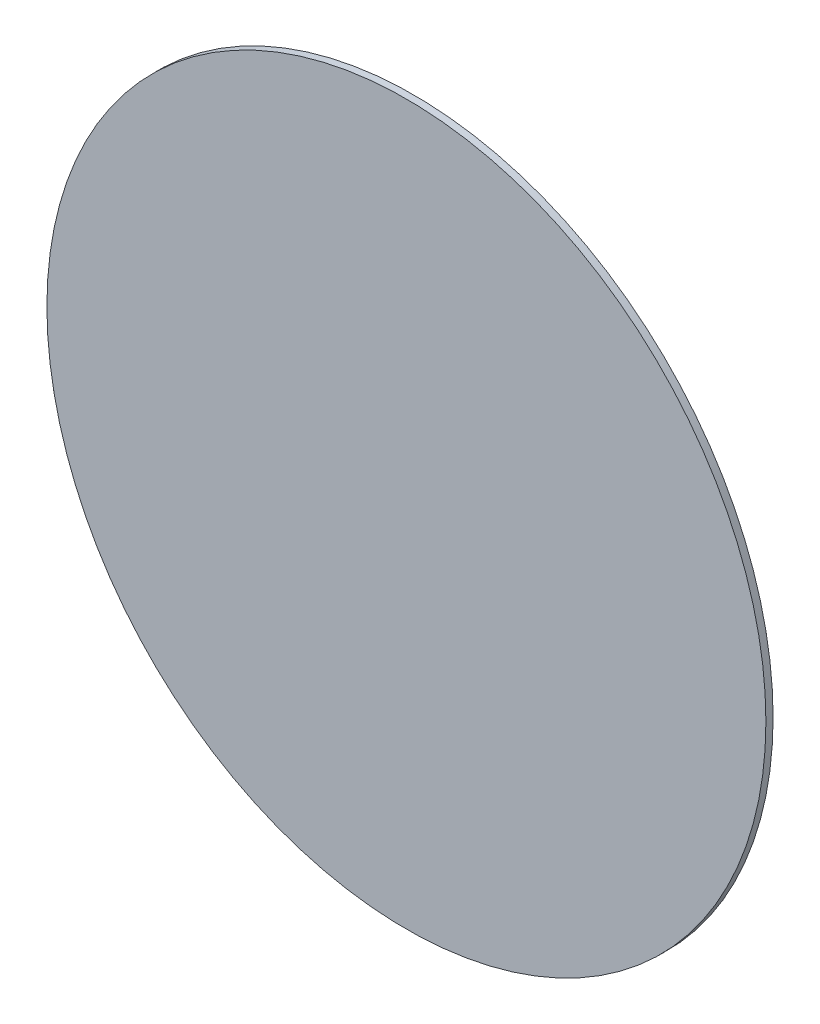
SolidWorks part; units mm, degrees
material "瓦楞纸"
ref_plane "前视基准面" through (0, 0, 0) normal (0, 0, 1) x (1, 0, 0)
ref_plane "上视基准面" through (0, 0, 0) normal (0, 1, 0) x (1, 0, 0)
ref_plane "右视基准面" through (0, 0, 0) normal (1, 0, 0) x (0, 0, -1)
sketch "Sketch1" plane through (0, 0, 0) normal (0, 0, 1) x (1, 0, 0)
  circle A0 centre (0, 0) radius 25
  dimension "D1" = 50
extrude "Extrude1" add sketch "Sketch1" along normal blind 0.5
